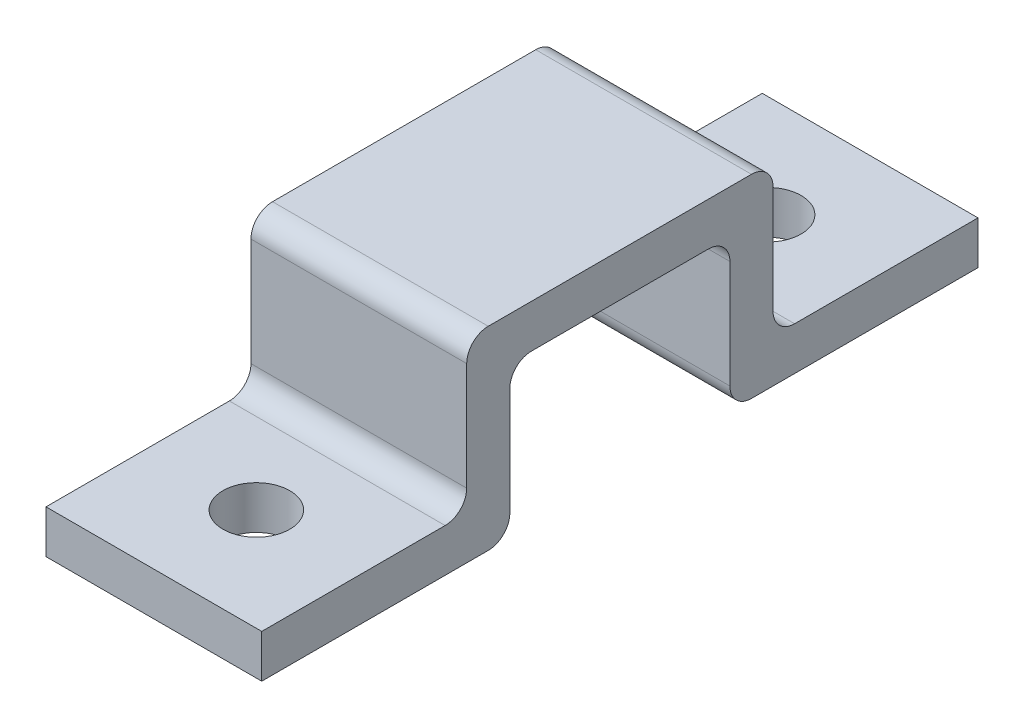
SolidWorks part; units mm, degrees
ref_plane "Front Plane" through (0, 0, 0) normal (0, 0, 1) x (1, 0, 0)
ref_plane "Top Plane" through (0, 0, 0) normal (0, 1, 0) x (1, 0, 0)
ref_plane "Right Plane" through (0, 0, 0) normal (1, 0, 0) x (0, 0, -1)
sketch "Sketch1" plane through (0, 0, 0) normal (1, 0, 0) x (0, 0, -1)
  line L0 (0, 0) -> (0, 14.0645) construction
  line L1 (-10.2, 0) -> (10.2, 0)
  line L2 (10.2, 0) -> (10.2, -14)
  line L3 (10.2, -14) -> (33.2, -14)
  line L4 (33.2, -14) -> (33.2, -10)
  line L5 (33.2, -10) -> (14.2, -10)
  line L6 (14.2, -10) -> (14.2, 4)
  line L7 (14.2, 4) -> (-14.2, 4)
  line L8 (-14.2, -10) -> (-14.2, 4)
  line L9 (-33.2, -10) -> (-14.2, -10)
  line L10 (-33.2, -14) -> (-33.2, -10)
  line L11 (-10.2, -14) -> (-33.2, -14)
  line L12 (-10.2, 0) -> (-10.2, -14)
  point P12 (0, 4)
  dimension "D1" = 10.2
  dimension "D2" = 14.2
  dimension "D3" = 4
  dimension "D4" = 23
  dimension "D5" = 14
  dimension "D6" = 4
extrude "Boss-Extrude1" add sketch "Sketch1" along normal blind 20
sketch "Sketch2" plane through (0, -10, 0) normal (0, 1, 0) x (1, 0, 0)
  line L0 (20, 33.2) -> (0, 33.2) construction
  line L1 (10, 33.2) -> (10, 14.2) construction
  line L2 (20, 14.2) -> (0, 14.2) construction
  circle A0 centre (10, 23.7) radius 3.1
  dimension "D1" = 6.2
extrude "Cut-Extrude1" cut sketch "Sketch2" against normal up to surface (4 mm away) up to face at (10, -14, -21.7)
mirror "Mirror1" about plane through (0, 0, 0) normal (0, 0, 1) of "Cut-Extrude1"
fillet "Fillet1" radius 2 8 edges at (10, -10, -14.2) (10, -10, 14.2) (10, 4, 14.2) (10, 4, -14.2) (10, 0, 10.2) (10, 0, -10.2) (10, -14, 10.2) (10, -14, -10.2)
